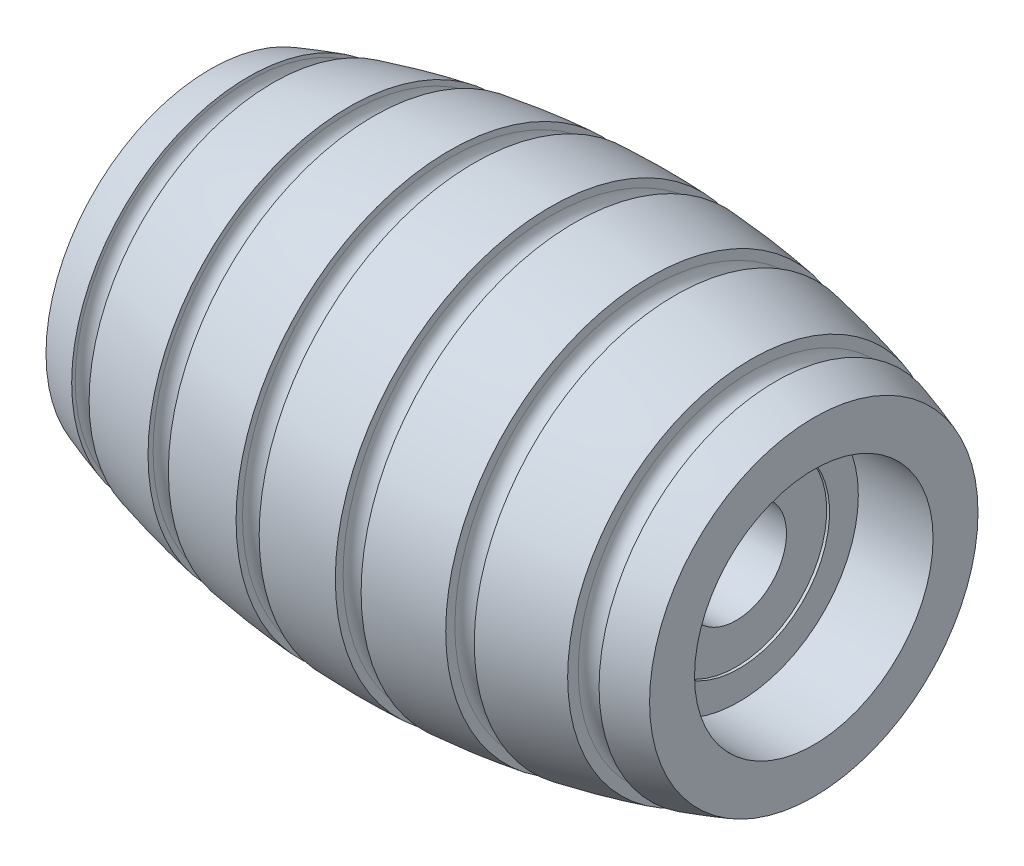
SolidWorks part; units mm, degrees
ref_plane "Front Plane" through (0, 0, 0) normal (0, 0, 1) x (1, 0, 0)
ref_plane "Top Plane" through (0, 0, 0) normal (0, 1, 0) x (1, 0, 0)
ref_plane "Right Plane" through (0, 0, 0) normal (1, 0, 0) x (0, 0, -1)
sketch "Sketch1" plane through (0, 0, 0) normal (0, 0, 1) x (1, 0, 0)
  line L0 (-24.5, 0) -> (45, 0) construction
  line L1 (-21, 11.427) -> (-21, 8.3)
  line L2 (-21, 8.3) -> (-15.8, 8.3)
  line L3 (-15.8, 8.3) -> (-15.8, 3.5) construction
  line L4 (-15.8, 3.5) -> (15.8, 3.5) construction
  line L5 (15.8, 3.5) -> (15.8, 8.3) construction
  line L6 (15.8, 8.3) -> (21, 8.3)
  line L7 (21, 8.3) -> (21, 11.427)
  line L8 (0, 0) -> (0, 41.0714) construction
  line L9 (-15.8, 8.3) -> (-15.8, 6.3)
  line L10 (-15.8, 6.3) -> (-15.6, 6.3)
  line L11 (-15.6, 6.3) -> (-15.6, 3.5)
  line L12 (-15.6, 3.5) -> (15.6, 3.5)
  line L13 (15.6, 3.5) -> (15.6, 6.3)
  line L14 (15.6, 6.3) -> (15.8, 6.3)
  line L15 (15.8, 6.3) -> (15.8, 8.3)
  line L16 (-17.5, 22.912) -> (-17.5, 13.9522) construction
  line L17 (-10.5, 15.2614) -> (-10.5, 22.912) construction
  line L18 (-3.5, 22.912) -> (-3.5, 16.0251) construction
  line L19 (3.5, 22.912) -> (3.5, 16.3775) construction
  line L20 (10.5, 16.3775) -> (10.5, 22.912) construction
  line L21 (17.5, 22.912) -> (17.5, 14.2835) construction
  line L22 (-24.5, 22.912) -> (-24.5, 12.1189) construction
  line L23 (24.5, 12.1189) -> (24.5, 22.912) construction
  line L24 (24.5, 22.912) -> (17.5, 22.912) construction
  line L25 (3.5, 22.912) -> (-3.5, 22.912) construction
  line L26 (-3.5, 22.912) -> (-10.5, 22.912) construction
  line L27 (-10.5, 22.912) -> (-17.5, 22.912) construction
  line L28 (-17.5, 22.912) -> (-24.5, 22.912) construction
  line L29 (3.5, 22.912) -> (10.5, 22.912) construction
  line L30 (10.5, 22.912) -> (17.5, 22.912) construction
  line L31 (-18.35, 12.2909) -> (-18.35, 12.041) construction
  line L32 (-18.35, 12.041) -> (-16.65, 12.041) construction
  line L33 (-16.65, 12.041) -> (-16.65, 12.7783) construction
  line L34 (-11.35, 13.9774) -> (-11.35, 13.6259) construction
  line L35 (-11.35, 13.6259) -> (-9.65, 13.6259) construction
  line L36 (-9.65, 13.6259) -> (-9.65, 14.2625) construction
  line L37 (-4.35, 14.8508) -> (-4.35, 14.4035) construction
  line L38 (-4.35, 14.4035) -> (-2.65, 14.4035) construction
  line L39 (-2.65, 14.4035) -> (-2.65, 14.9447) construction
  line L40 (2.65, 14.9447) -> (2.65, 14.4035) construction
  line L41 (2.65, 14.4035) -> (4.35, 14.4035) construction
  line L42 (4.35, 14.4035) -> (4.35, 14.8508) construction
  line L43 (9.65, 14.2625) -> (9.65, 13.6259) construction
  line L44 (9.65, 13.6259) -> (11.35, 13.6259) construction
  line L45 (11.35, 13.6259) -> (11.35, 13.9774) construction
  line L46 (16.65, 12.7783) -> (16.65, 12.041) construction
  line L47 (16.65, 12.041) -> (18.35, 12.041) construction
  line L48 (18.35, 12.041) -> (18.35, 12.2909) construction
  line L49 (-18.35, 12.2909) -> (-18.35, 12.041)
  line L50 (-16.65, 12.041) -> (-16.65, 12.7783)
  line L51 (-11.35, 13.9774) -> (-11.35, 13.6259)
  line L52 (-9.65, 13.6259) -> (-9.65, 14.2625)
  line L53 (-4.35, 14.8508) -> (-4.35, 14.4035)
  line L54 (-2.65, 14.4035) -> (-2.65, 14.9447)
  line L55 (2.65, 14.9447) -> (2.65, 14.4035)
  line L56 (4.35, 14.4035) -> (4.35, 14.8508)
  line L57 (9.65, 14.2625) -> (9.65, 13.6259)
  line L58 (11.35, 13.6259) -> (11.35, 13.9774)
  line L59 (16.65, 12.7783) -> (16.65, 12.041)
  line L60 (18.35, 12.041) -> (18.35, 12.2909)
  line L61 (-17.5, 12.041) -> (-17.5, 12.541) construction
  line L62 (-10.5, 14.1259) -> (-10.5, 13.6259) construction
  line L63 (-3.5, 14.9035) -> (-3.5, 14.4035) construction
  line L64 (3.5, 14.9035) -> (3.5, 14.4035) construction
  line L65 (10.5, 14.1259) -> (10.5, 13.6259) construction
  line L66 (17.5, 12.541) -> (17.5, 12.041) construction
  arc A0 (-21, 11.427) -> (21, 11.427) centre (0, -48.5) cw construction
  arc A1 (-18.35, 12.041) -> (-16.65, 12.041) centre (-17.5, 12.041) ccw
  arc A2 (-21, 11.427) -> (-18.35, 12.2909) centre (0, -48.5) cw
  arc A3 (-11.35, 13.6259) -> (-9.65, 13.6259) centre (-10.5, 13.6259) ccw
  arc A4 (-4.35, 14.4035) -> (-2.65, 14.4035) centre (-3.5, 14.4035) ccw
  arc A5 (2.65, 14.4035) -> (4.35, 14.4035) centre (3.5, 14.4035) ccw
  arc A6 (9.65, 13.6259) -> (11.35, 13.6259) centre (10.5, 13.6259) ccw
  arc A7 (16.65, 12.041) -> (18.35, 12.041) centre (17.5, 12.041) ccw
  arc A8 (-16.65, 12.7783) -> (-11.35, 13.9774) centre (0, -48.5) cw
  arc A9 (-9.65, 14.2625) -> (-4.35, 14.8508) centre (0, -48.5) cw
  arc A10 (-2.65, 14.9447) -> (2.65, 14.9447) centre (0, -48.5) cw
  arc A11 (4.35, 14.8508) -> (9.65, 14.2625) centre (0, -48.5) cw
  arc A12 (11.35, 13.9774) -> (16.65, 12.7783) centre (0, -48.5) cw
  arc A13 (18.35, 12.2909) -> (21, 11.427) centre (0, -48.5) cw
  point P16 (0, 15)
  point P73 (-10.5, 14.1259)
  point P75 (-3.5, 14.9035)
  point P76 (3.5, 14.9035)
  point P77 (10.5, 14.1259)
  point P78 (17.5, 12.541)
  point P79 (-17.5, 12.541)
  dimension "D5" = 63.5
  dimension "D7" = 0.2
  dimension "D1" = 3.5
  dimension "D2" = 8.3
  dimension "D3" = 5.2
  dimension "D4" = 15
  dimension "D6" = 42
  dimension "D8" = 2
  dimension "D9" = 1.7
  dimension "D10" = 0.5
  dimension "D11" = 12.041
  dimension "D12" = 14.4035
revolve "Revolve1" add sketch "Sketch1" angle 360 about L0
